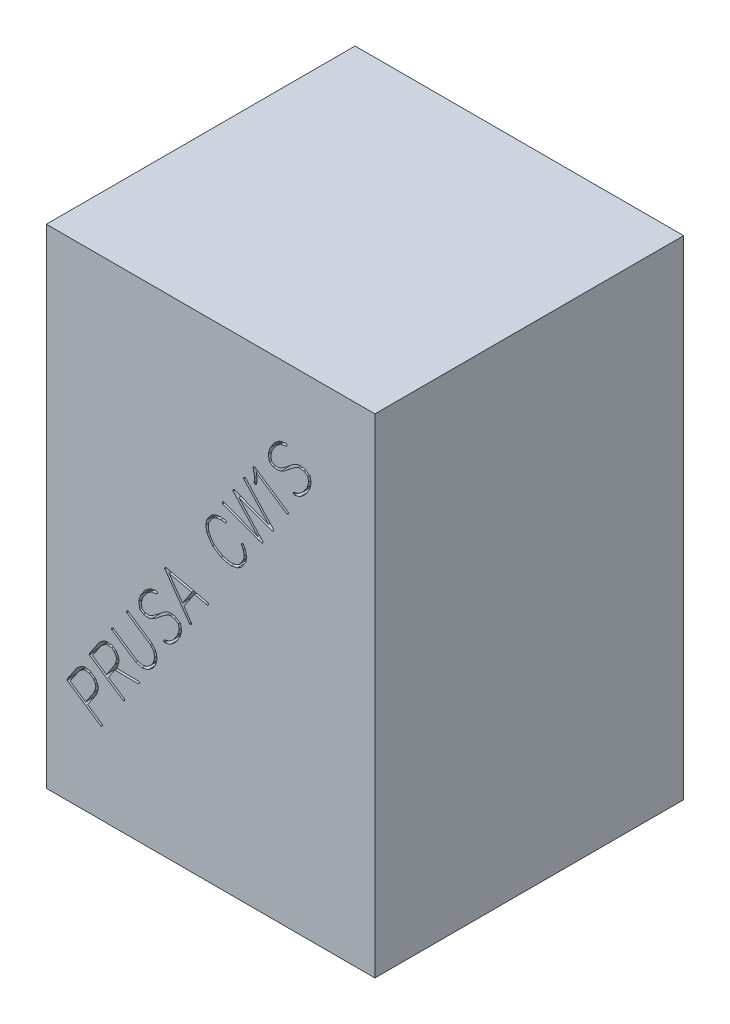
SolidWorks part; units mm, degrees
ref_plane "Front Plane" through (0, 0, 0) normal (0, 0, 1) x (1, 0, 0)
ref_plane "Top Plane" through (0, 0, 0) normal (0, 1, 0) x (1, 0, 0)
ref_plane "Right Plane" through (0, 0, 0) normal (1, 0, 0) x (0, 0, -1)
sketch "Sketch1" plane through (0, 0, 0) normal (0, 1, 0) x (1, 0, 0)
  line L1 (-116, -109) -> (116, -109)
  line L2 (-116, -109) -> (-116, 109)
  line L3 (-116, 109) -> (116, 109)
  line L4 (116, -109) -> (116, 109)
  line L5 (-116, -109) -> (116, 109) construction
  line L6 (-116, 109) -> (116, -109) construction
  point P0 (0, 0)
  dimension "D1" = 218
  dimension "D2" = 232
extrude "Boss-Extrude1" add sketch "Sketch1" along normal blind 345
sketch "Sketch2" plane through (0, 0, 109) normal (0, 0, 1) x (1, 0, 0)
  line L0 (-116, 0) -> (116, 345) construction
  text T0 "PRUSA CW1S" font "SWSimp" height 30
extrude "Cut-Extrude1" cut sketch "Sketch2" against normal blind 10
